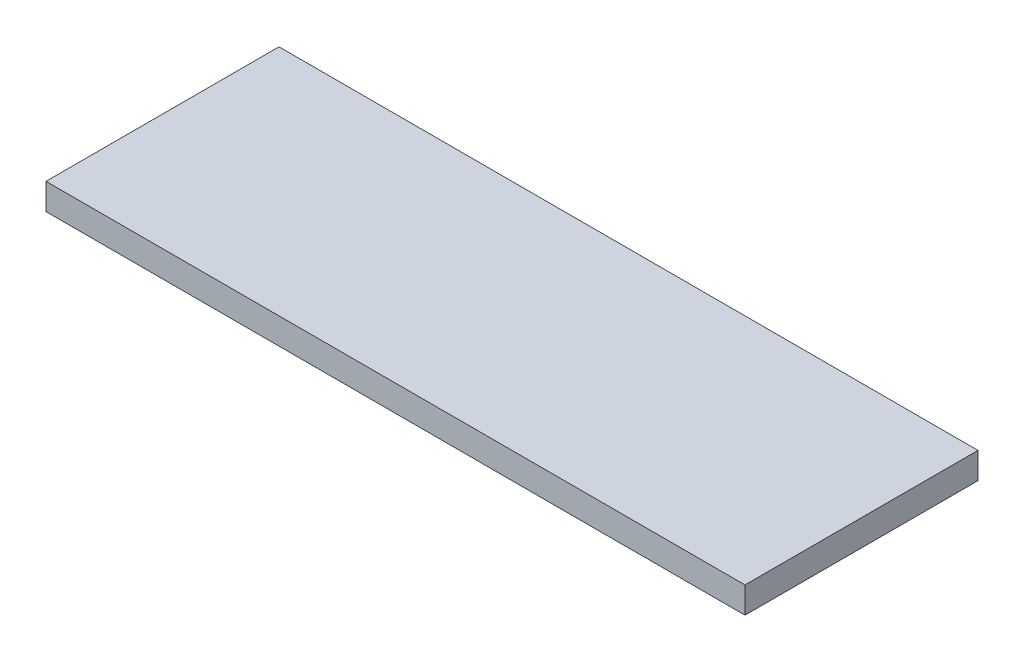
SolidWorks part; units mm, degrees
ref_plane "前视基准面" through (0, 0, 0) normal (0, 0, 1) x (1, 0, 0)
ref_plane "上视基准面" through (0, 0, 0) normal (0, 1, 0) x (1, 0, 0)
ref_plane "右视基准面" through (0, 0, 0) normal (1, 0, 0) x (0, 0, -1)
other "Configuration Table"
sketch "草图1" plane through (0, 0, 0) normal (0, 1, 0) x (1, 0, 0)
  line L1 (0, 0) -> (120, 0)
  line L2 (0, 0) -> (0, 40)
  line L3 (0, 40) -> (120, 40)
  line L4 (120, 0) -> (120, 40)
  dimension "D1" = 40
  dimension "D2" = 120
extrude "凸台-拉伸1" add sketch "草图1" along normal blind 4.5
